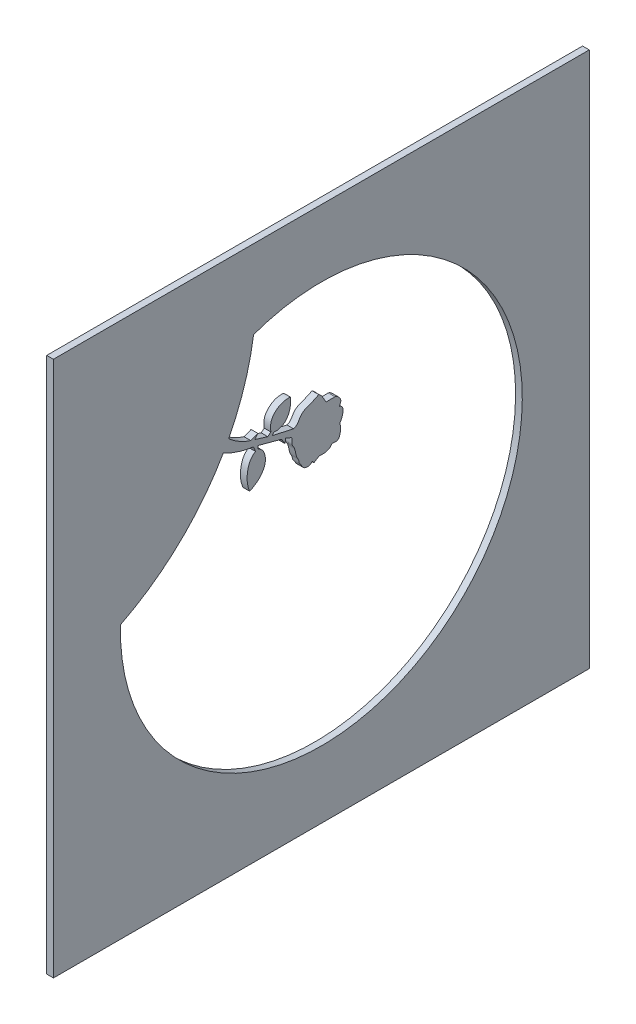
SolidWorks part; units mm, degrees
ref_plane "Plan de face" through (0, 0, 0) normal (0, 0, 1) x (1, 0, 0)
ref_plane "Plan de dessus" through (0, 0, 0) normal (0, 1, 0) x (1, 0, 0)
ref_plane "Plan de droite" through (0, 0, 0) normal (1, 0, 0) x (0, 0, -1)
sketch "Esquisse1" plane through (0, 0, 0) normal (1, 0, 0) x (0, 0, -1)
  line L1 (-200, 200) -> (200, 200)
  line L2 (-200, 200) -> (-200, -200)
  line L3 (-200, -200) -> (200, -200)
  line L4 (200, 200) -> (200, -200)
  line L5 (-200, 200) -> (200, -200) construction
  line L6 (-200, -200) -> (200, 200) construction
  circle A0 centre (0, 0) radius 150
  dimension "D1" = 300
  dimension "D2" = 400
  dimension "D3" = 400
extrude "Boss.-Extru.1" add sketch "Esquisse1" along normal blind 5
sketch "Esquisse2" plane through (5, 0, 0) normal (1, 0, 0) x (0, 0, -1)
  arc A0 (-149.9631, 3.3263) -> (-50.5824, 141.2141) centre (-232.7961, 167.7846) ccw
  circle A1 centre (0, 0) radius 150 construction
  arc A2 (-149.9631, 3.3263) -> (-50.5824, 141.2141) centre (0, 0) cw
  point P6 (-10.2541, 149.6491)
  point P7 (-128.8659, 139.3613)
  point P8 (-42.7177, 143.7887)
  point P9 (-149.9631, 3.3263)
  point P10 (-50.5824, 141.2141)
extrude "Boss.-Extru.2" add sketch "Esquisse2" against normal up to vertex (5 mm away) up to point (0, -200, -200)
sketch "Esquisse3" plane through (5, 0, 0) normal (1, 0, 0) x (0, 0, -1)
  line L7 (-50.6418, 68.697) -> (-49.1213, 64.9501)
  line L8 (-47.1519, 65.3947) -> (-47.4739, 67.92)
  line L9 (-47.4739, 67.92) -> (-29.7711, 63.144)
  line L10 (-29.7711, 63.144) -> (-27.1628, 59.0834)
  line L11 (-27.1628, 59.0834) -> (-26.6394, 62.3226)
  line L12 (-26.6394, 62.3226) -> (-22.1216, 60.423)
  line L13 (-6.8667, 37.5362) -> (-5.5134, 35.8348)
  line L14 (-5.5134, 35.8348) -> (-1.7688, 38.2434)
  line L15 (-1.7688, 38.2434) -> (2.6138, 38.2434)
  line L16 (2.6138, 38.2434) -> (6.4683, 39.7138)
  line L17 (6.4683, 39.7138) -> (8.185, 41.6499)
  line L18 (8.185, 41.6499) -> (11.4457, 41.2751)
  line L19 (10.117, 70.6322) -> (3.4944, 70.6322)
  line L20 (-20.7332, 65.3947) -> (-36.7316, 68.9665)
  line L21 (-36.7316, 68.9665) -> (-35.2546, 70.6322)
  line L22 (-37.6461, 71.8238) -> (-39.9879, 69.961)
  line L23 (-39.9879, 69.961) -> (-49.7055, 72.945)
  line L24 (-49.7055, 72.945) -> (-47.4739, 75.8652)
  line L25 (-47.4739, 75.8652) -> (-52.7288, 73.8109)
  line L26 (-82.8305, 97.7067) -> (-88.3694, 87.035)
  spline S0 degree 2 poles (-88.3694, 87.035) (-72.2806, 71.6186) (-50.6418, 68.697) knots 0 0 0 1 1 1
  spline S1 degree 3 poles (-49.1213, 64.9501) (-52.5108, 63.0931) (-56.251, 54.8742) (-55.436, 45.9735) (-53.5444, 41.4606) knots 0 0 0 0 0.427817 1 1 1 1
  spline S2 degree 3 poles (-53.5444, 41.4606) (-49.4938, 43.1439) (-43.6778, 47.5517) (-40.651, 57.7265) (-43.6875, 64.2086) (-47.1519, 65.3947) knots 0 0 0 0 0.433456 0.652392 1 1 1 1
  spline S3 degree 3 poles (-22.1216, 60.423) (-21.9007, 58.8444) (-22.5939, 56.1889) (-20.434, 53.4243) (-19.1578, 49.9008) (-18.8937, 46.0147) (-16.716, 43.3731) (-16.7612, 40.9958) (-14.9325, 39.2509) (-13.2215, 35.2207) (-8.354, 34.95) (-6.8667, 37.5362) knots 0 0 0 0 0.150869 0.214819 0.309773 0.49168 0.556112 0.609109 0.695847 0.772435 1 1 1 1
  spline S4 degree 3 poles (11.4457, 41.2751) (12.917, 41.7295) (14.6821, 45.7528) (14.2481, 49.6304) (13.9428, 52.1546) knots 0 0 0 0 0.363892 1 1 1 1
  spline S5 degree 3 poles (13.9428, 52.1546) (15.1067, 53.4238) (15.813, 55.8439) (16.5783, 59.8925) (15.3239, 62.438) (13.4956, 62.7952) knots 0 0 0 0 0.408733 0.602432 1 1 1 1
  spline S6 degree 3 poles (13.4956, 62.7952) (13.9701, 63.803) (15.7053, 67.1846) (12.0415, 70.2874) (10.117, 70.6322) knots 0 0 0 0 0.344176 1 1 1 1
  spline S7 degree 3 poles (3.4944, 70.6322) (1.7864, 73.2438) (0.8416, 76.3831) (-1.9846, 78.1549) knots 0 0 0 0 1 1 1 1
  spline S8 degree 3 poles (-1.9846, 78.1549) (-4.6197, 76.4855) (-9.2559, 75.2504) (-16.5194, 71.5681) (-17.4801, 66.153) (-20.7332, 65.3947) knots 0 0 0 0 0.395717 0.631603 1 1 1 1
  spline S9 degree 3 poles (-35.2546, 70.6322) (-33.2631, 70.2108) (-28.029, 72.174) (-27.3395, 72.7308) (-25.2991, 75.2062) (-23.1541, 79.1092) (-22.6372, 84.198) (-23.0015, 87.035) knots 0 0 0 0 0.051638 0.199516 0.247018 0.508164 1 1 1 1
  spline S10 degree 3 poles (-23.0015, 87.035) (-27.1424, 87.753) (-32.8082, 85.5718) (-38.0942, 78.9177) (-38.0867, 74.3416) (-37.6461, 71.8238) knots 0 0 0 0 0.488971 0.684624 1 1 1 1
  spline S11 degree 3 poles (-52.7288, 73.8109) (-65.2902, 77.4167) (-74.9095, 88.0955) (-82.8305, 97.7067) knots 0 0 0 0 1 1 1 1
  point P7 (-51.3533, 78.0644)
  point P8 (0, 0)
  point P9 (-71.5423, 84.2899)
  point P77 (0, 0)
  point P79 (-45.8424, 83.5753)
  point P81 (0, 0)
  point P82 (-66.0034, 94.9616)
  point P83 (-46.9338, 78.3449)
  point P84 (-50.8901, 79.2481)
  point P85 (-50.0197, 70.1998)
  point P86 (-30.6469, 73.1201)
  point P87 (-10.3358, 56.3383)
  point P88 (9.9603, 34.7911)
  point P89 (15.0582, 35.4983)
  point P90 (0, 0)
  point P91 (-21.6922, 64.3673)
  point P92 (-36.2135, 69.6048)
  point P93 (-26.6394, 73.5839)
  point P94 (-23.9528, 78.1549)
  point P95 (0, 0)
  point P96 (-32.1207, 70.6972)
extrude "Boss.-Extru.3" add sketch "Esquisse3" against normal up to vertex (5 mm away) up to point (0, -200, -200)
sketch "Esquisse4" plane through (5, 0, 0) normal (1, 0, 0) x (0, 0, -1)
  line L0 (-84.656, 58.4121) -> (-5.9681, 19.4497)
  line L1 (-55.8839, 116.6974) -> (22.8746, 77.7)
  line L2 (22.8746, 77.7) -> (-5.9681, 19.4497) construction
  line L3 (-87.3184, 53.0351) -> (-8.6305, 14.0727)
  line L4 (-11.0692, 101.2025) -> (25.537, 83.0769)
  line L5 (-87.3184, 53.0351) -> (-88.3682, 53.555)
  line L6 (-88.3682, 53.555) -> (-84.656, 58.4121)
  line L9 (-13.7316, 95.8256) -> (22.8746, 77.7) construction
  line L10 (-11.0692, 101.2025) -> (-54.2849, 122.6008)
  line L11 (-54.2849, 122.6008) -> (-55.8839, 116.6974)
  arc A0 (-149.9631, 3.3263) -> (-73.2046, 75.9239) centre (-232.7961, 167.7846) ccw construction
  arc A1 (-69.2112, 83.2398) -> (-50.5824, 141.2141) centre (-232.7961, 167.7846) ccw construction
  arc A2 (-5.9681, 19.4497) -> (22.8746, 77.7) centre (8.4532, 48.5748) ccw
  arc A3 (-8.6305, 14.0727) -> (25.537, 83.0769) centre (8.4532, 48.5748) ccw
  arc A4 (-5.9681, 19.4497) -> (22.8746, 77.7) centre (8.4532, 48.5748) ccw construction
  point P10 (0, 0)
  point P11 (-51.3005, 115.8262)
  point P18 (0, 0)
  point P19 (0, 0)
  point P20 (-91.2929, 54.4576)
  point P22 (0, 27.0131)
  point P23 (31.0034, 116.3827)
  point P24 (-44.7623, 129.6334)
  point P25 (-50.279, 118.4629)
  point P26 (-72.9186, 74.6684)
  point P27 (-52.7623, 112.2478)
  point P28 (-51.8276, 114.5112)
  point P29 (-90.7985, 54.1436)
  point P30 (-84.656, 58.4121)
  dimension "D2" = 65
  dimension "D1" = 6
